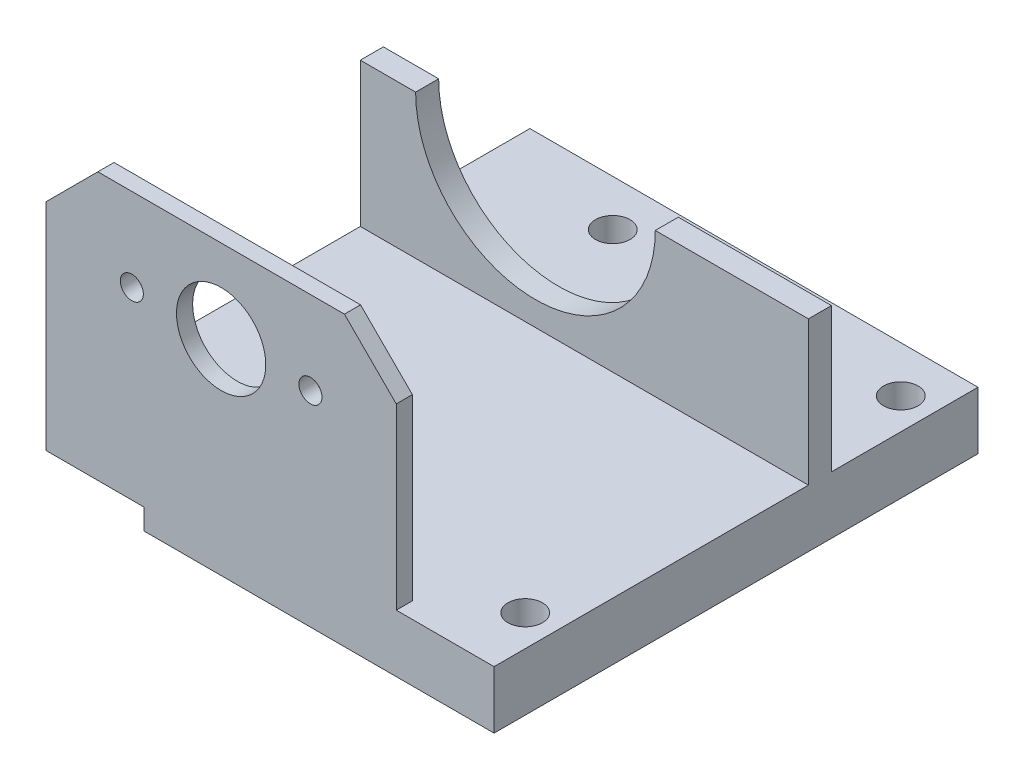
SolidWorks part; units mm, degrees
ref_plane "Front Plane" through (0, 0, 0) normal (0, 0, 1) x (1, 0, 0)
ref_plane "Top Plane" through (0, 0, 0) normal (0, 1, 0) x (1, 0, 0)
ref_plane "Right Plane" through (0, 0, 0) normal (1, 0, 0) x (0, 0, -1)
sketch "Sketch1" plane through (0, 0, 0) normal (0, 1, 0) x (1, 0, 0)
  line L1 (-15.2, 21) -> (15.2, 21)
  line L2 (-15.2, 21) -> (-15.2, -21)
  line L3 (-15.2, -21) -> (15.2, -21)
  line L4 (15.2, 21) -> (15.2, -21)
  line L5 (-15.2, 21) -> (15.2, -21) construction
  line L6 (-15.2, -21) -> (15.2, 21) construction
  point P0 (0, 0)
  dimension "D1" = 30.4
  dimension "D2" = 42
extrude "Boss-Extrude1" add sketch "Sketch1" along normal blind 5
sketch "Sketch2" plane through (-15.2, 0, 0) normal (-1, 0, 0) x (0, 0, 1)
  line L0 (21, 5) -> (21, 0) construction
  line L1 (-21, 5) -> (21, 5)
  line L2 (-21, 5) -> (-21, 1.8)
  line L3 (-21, 1.8) -> (21, 1.8)
  line L4 (21, 5) -> (21, 1.8)
  dimension "D1" = 3.2
extrude "Boss-Extrude2" add sketch "Sketch2" along normal blind 8.49
sketch "Sketch4" plane through (0, 5, 0) normal (0, 1, 0) x (1, 0, 0)
  line L1 (-23.69, -21) -> (6.71, -21)
  line L2 (-23.69, -21) -> (-23.69, -19.6)
  line L3 (-23.69, -19.6) -> (6.71, -19.6)
  line L4 (6.71, -21) -> (6.71, -19.6)
  dimension "D1" = 30.4
  dimension "D2" = 1.4
extrude "Boss-Extrude3" add sketch "Sketch4" along normal blind 20
sketch "Sketch5" plane through (0, 0, 19.6) normal (0, 0, -1) x (-1, 0, 0)
  line L0 (-6.71, 17.78) -> (23.69, 17.78) construction
  line L1 (-6.71, 25) -> (-6.71, 5) construction
  line L2 (23.69, 25) -> (23.69, 5) construction
  line L3 (-6.71, 25) -> (23.69, 25) construction
  line L4 (8.49, 25) -> (8.49, 5) construction
  line L5 (-6.71, 5) -> (23.69, 5) construction
  circle A0 centre (8.49, 17.78) radius 3.875
  circle A1 centre (0.74, 17.78) radius 1
  circle A2 centre (16.24, 17.78) radius 1
  dimension "D2" = 7.75
  dimension "D3" = 2
  dimension "D4" = 2
  dimension "D1" = 7.22
  dimension "D5" = 7.75
  dimension "D6" = 7.75
extrude "Cut-Extrude1" cut sketch "Sketch5" against normal blind 1.4
chamfer "Chamfer1" distance 4.5 angle 45 2 edges at (-23.69, 25, 20.3) (6.71, 25, 20.3)
sketch "Sketch6" plane through (0, 5, 0) normal (0, 1, 0) x (1, 0, 0)
  line L0 (6.71, -21) -> (15.2, -21) construction
  line L1 (15.2, -21) -> (15.2, 21) construction
  circle A0 centre (12.5, -15.6) radius 1.5
  circle A1 centre (12.5, 17) radius 1.5
  circle A2 centre (-12.5, 17) radius 1.5
  circle A3 centre (-12.5, -15.6) radius 1.5
  dimension "D3" = 3
  dimension "D4" = 32.6
  dimension "D5" = 25
  dimension "D1" = 5.4
  dimension "D2" = 2.7
extrude "Cut-Extrude2" cut sketch "Sketch6" against normal blind 5
sketch "Sketch7" plane through (0, 5, 0) normal (0, 1, 0) x (1, 0, 0)
  line L0 (-23.69, 8.28) -> (15.2, 8.28) construction
  line L1 (-23.69, -19.6) -> (-23.69, 21) construction
  line L2 (15.2, -21) -> (15.2, 21) construction
  line L3 (15.2, 21) -> (-23.69, 21) construction
  line L5 (-23.69, 8.28) -> (15.2, 8.28)
  line L6 (-23.69, 8.28) -> (-23.69, 6.28)
  line L7 (-23.69, 6.28) -> (15.2, 6.28)
  line L8 (15.2, 8.28) -> (15.2, 6.28)
  dimension "D1" = 12.72
  dimension "D2" = 2
extrude "Boss-Extrude4" add sketch "Sketch7" along normal blind 12.5
sketch "Sketch8" plane through (0, 0, -8.28) normal (0, 0, -1) x (-1, 0, 0)
  line L0 (23.69, 13.4303) -> (-6.71, 13.4303) construction
  line L1 (23.69, 17.5) -> (23.69, 5) construction
  line L2 (8.49, 13.4303) -> (8.49, 17.5) construction
  line L3 (-15.2, 17.5) -> (23.69, 17.5) construction
  circle A0 centre (8.49, 17.5) radius 10.4
  dimension "D2" = 20.8
  dimension "D1" = 30.4
extrude "Cut-Extrude3" cut sketch "Sketch8" against normal blind 2
